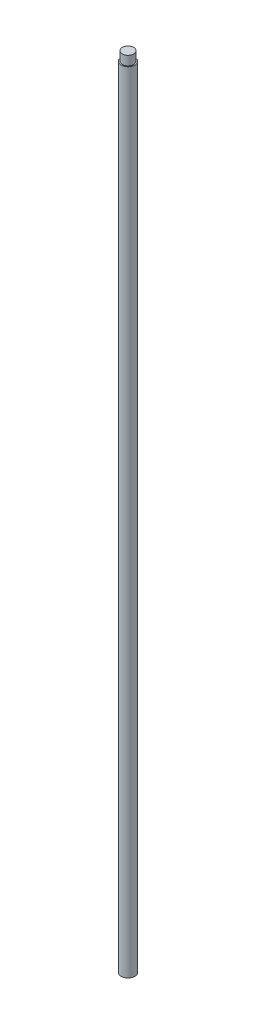
SolidWorks part; units mm, degrees
ref_plane "Front Plane" through (0, 0, 0) normal (0, 0, 1) x (1, 0, 0)
ref_plane "Top Plane" through (0, 0, 0) normal (0, 1, 0) x (1, 0, 0)
ref_plane "Right Plane" through (0, 0, 0) normal (1, 0, 0) x (0, 0, -1)
sketch "Sketch1" plane through (0, 0, 0) normal (0, 1, 0) x (1, 0, 0)
  circle A0 centre (0, 0) radius 6
  dimension "D1" = 12
extrude "Extrude1" add sketch "Sketch1" against normal blind 700
sketch "Sketch2" plane through (0, 0, 0) normal (0, 1, 0) x (1, 0, 0)
  circle A0 centre (0, 0) radius 6
  circle A1 centre (0, 0) radius 5
  circle A2 centre (0, 0) radius 6 construction
  dimension "D1" = 10
extrude "Extrude2" cut sketch "Sketch2" against normal blind 8
